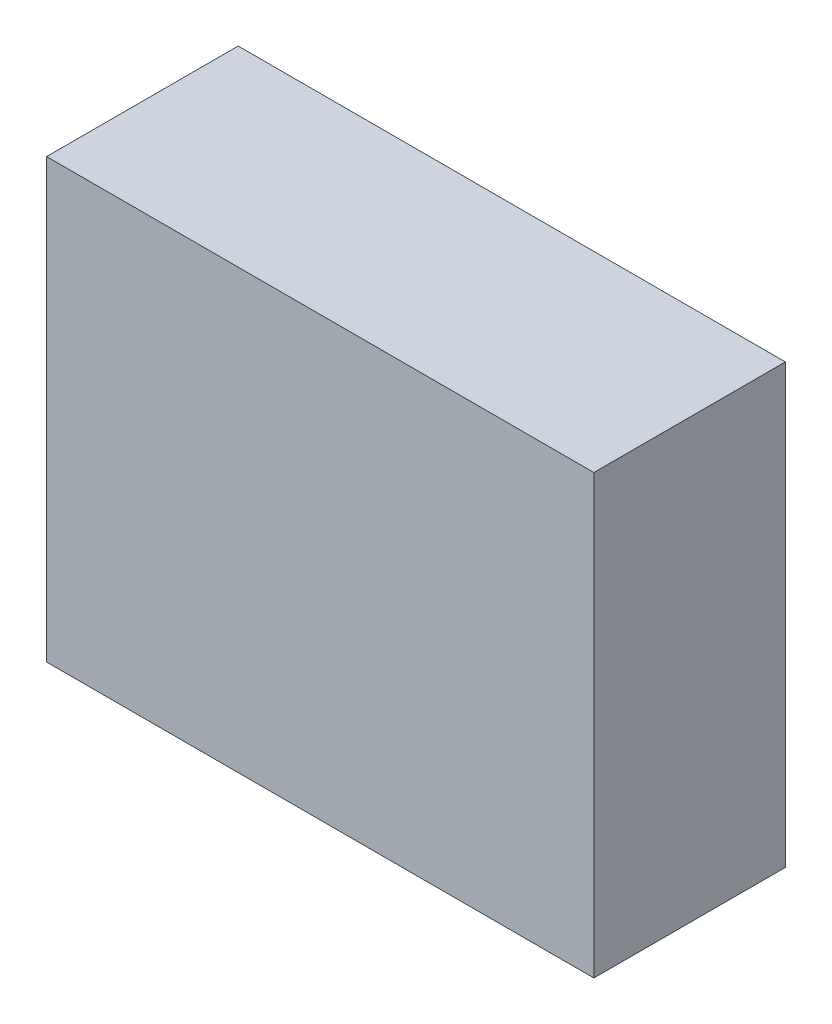
SolidWorks part; units mm, degrees
ref_plane "Front Plane" through (0, 0, 0) normal (0, 0, 1) x (1, 0, 0)
ref_plane "Top Plane" through (0, 0, 0) normal (0, 1, 0) x (1, 0, 0)
ref_plane "Right Plane" through (0, 0, 0) normal (1, 0, 0) x (0, 0, -1)
sketch "Sensor_envelope_5x4x1p75_Profile" plane through (0, 0, 0) normal (0, 0, 1) x (1, 0, 0)
  line L1 (10, -2) -> (15, -2)
  line L2 (10, -2) -> (10, 2)
  line L3 (10, 2) -> (15, 2)
  line L4 (15, -2) -> (15, 2)
extrude "Sensor_envelope_5x4x1p75" add sketch "Sensor_envelope_5x4x1p75_Profile" along normal blind 1.75 from offset 22.55
